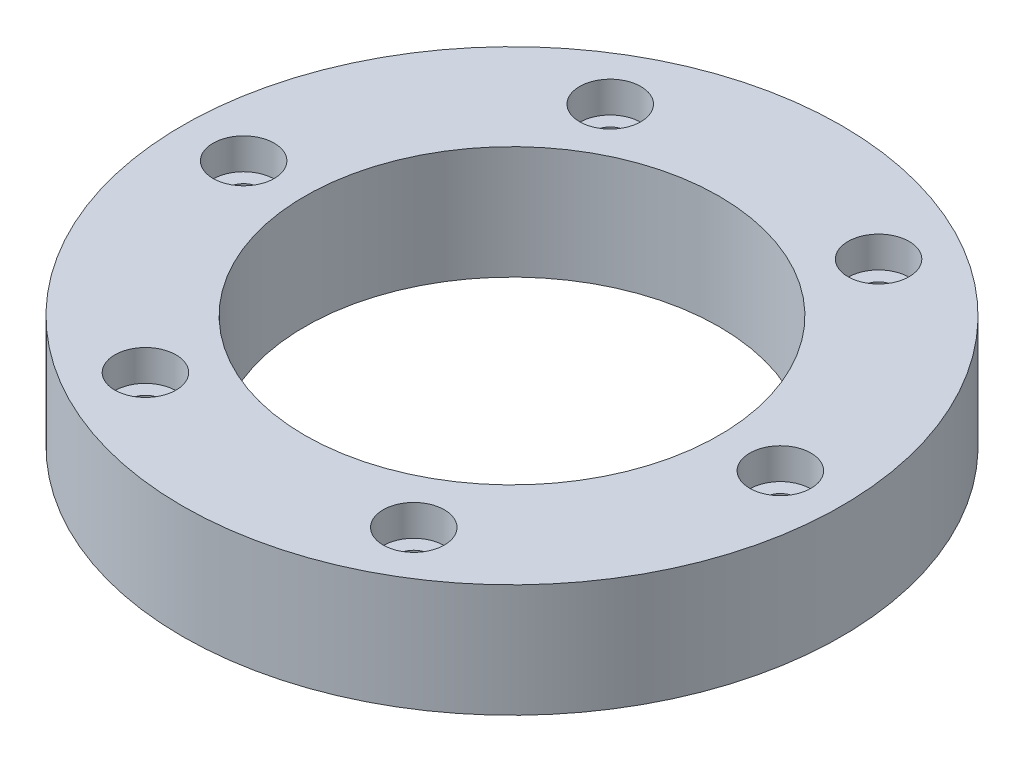
SolidWorks part; units mm, degrees
ref_plane "Front Plane" through (0, 0, 0) normal (0, 0, 1) x (1, 0, 0)
ref_plane "Top Plane" through (0, 0, 0) normal (0, 1, 0) x (1, 0, 0)
ref_plane "Right Plane" through (0, 0, 0) normal (1, 0, 0) x (0, 0, -1)
sketch "草图1" plane through (0, 0, 0) normal (0, 1, 0) x (1, 0, 0)
  circle A0 centre (0, 0) radius 35
  circle A1 centre (0, 0) radius 28.5 construction
  circle A2 centre (-28.5, 0) radius 1.7
  circle A3 centre (-14.25, 24.6817) radius 1.7
  circle A4 centre (14.25, 24.6817) radius 1.7
  circle A5 centre (28.5, 0) radius 1.7
  circle A6 centre (14.25, -24.6817) radius 1.7
  circle A7 centre (-14.25, -24.6817) radius 1.7
  circle A9 centre (0, 0) radius 22
  point P18 (0, 0)
  dimension "D1" = 70
  dimension "D2" = 57
  dimension "D3" = 3.4
  dimension "D5" = 6.5
  dimension "D4" = 6
extrude "凸台-拉伸1" add sketch "草图1" along normal blind 12
sketch "草图2" plane through (0, 12, 0) normal (0, 1, 0) x (1, 0, 0)
  circle A0 centre (-28.5, 0) radius 3.25
  circle A1 centre (-14.25, 24.6817) radius 3.25
  circle A2 centre (14.25, 24.6817) radius 3.25
  circle A3 centre (28.5, 0) radius 3.25
  circle A4 centre (14.25, -24.6817) radius 3.25
  circle A5 centre (-14.25, -24.6817) radius 3.25
  point P15 (0, 0)
  dimension "D1" = 6.5
  dimension "D2" = 6
extrude "切除-拉伸1" cut sketch "草图2" against normal blind 3.3
